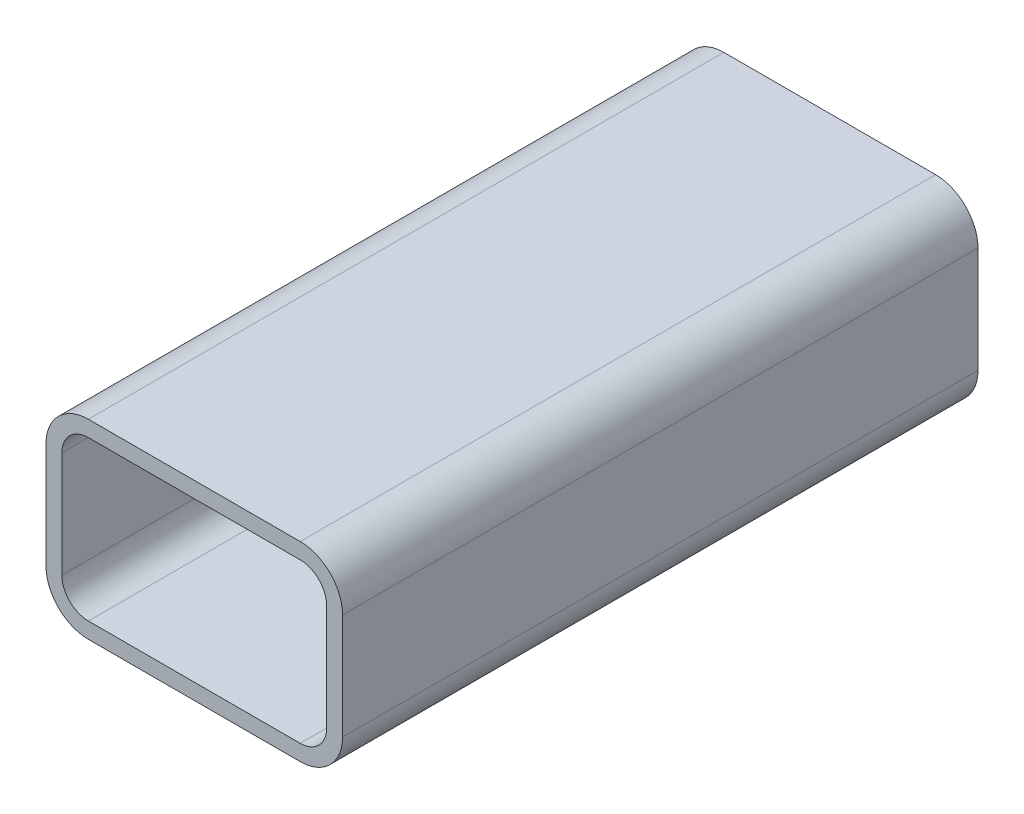
SolidWorks part; units mm, degrees
ref_plane "Front Plane" through (0, 0, 0) normal (0, 0, 1) x (1, 0, 0)
ref_plane "Top Plane" through (0, 0, 0) normal (0, 1, 0) x (1, 0, 0)
ref_plane "Right Plane" through (0, 0, 0) normal (1, 0, 0) x (0, 0, -1)
sketch "Sketch1" plane through (0, 0, 0) normal (0, 0, 1) x (1, 0, 0)
  line L1 (-20, -15) -> (20, -15)
  line L2 (-25, -10) -> (-25, 10)
  line L3 (-20, 15) -> (20, 15)
  line L4 (25, -10) -> (25, 10)
  line L5 (-25, -15) -> (25, 15) construction
  line L6 (-25, 15) -> (25, -15) construction
  arc A0 (-25, 10) -> (-20, 15) centre (-20, 10) cw
  arc A1 (-20, -15) -> (-25, -10) centre (-20, -10) cw
  arc A2 (25, -10) -> (20, -15) centre (20, -10) cw
  arc A3 (20, 15) -> (25, 10) centre (20, 10) cw
  point P0 (0, 0)
  dimension "D3" = 5
  dimension "D1" = 50
  dimension "D2" = 30
extrude "Extrude-Thin1" add sketch "Sketch1" along normal mid plane 120 thin
sketch "Sketch2" plane through (0, 18, 0) normal (0, 1, 0) x (1, 0, 0)
  line L1 (6, 45) -> (6, -45)
  line L3 (-6, -45) -> (-6, 45)
  line L4 (0, 35.9392) -> (0, -26.3418) construction
  line L5 (21.6452, 0) -> (-19.8074, 0) construction
  arc A0 (-6, 45) -> (6, 45) centre (0, 45) cw
  arc A1 (-6, -45) -> (6, -45) centre (0, -45) ccw
  point P10 (6, 0)
  dimension "D3" = 6
  dimension "D1" = 12
  dimension "D2" = 90
  dimension "D4" = 0
extrude "Cut-Extrude1" [suppressed] cut sketch "Sketch2" against normal through all
